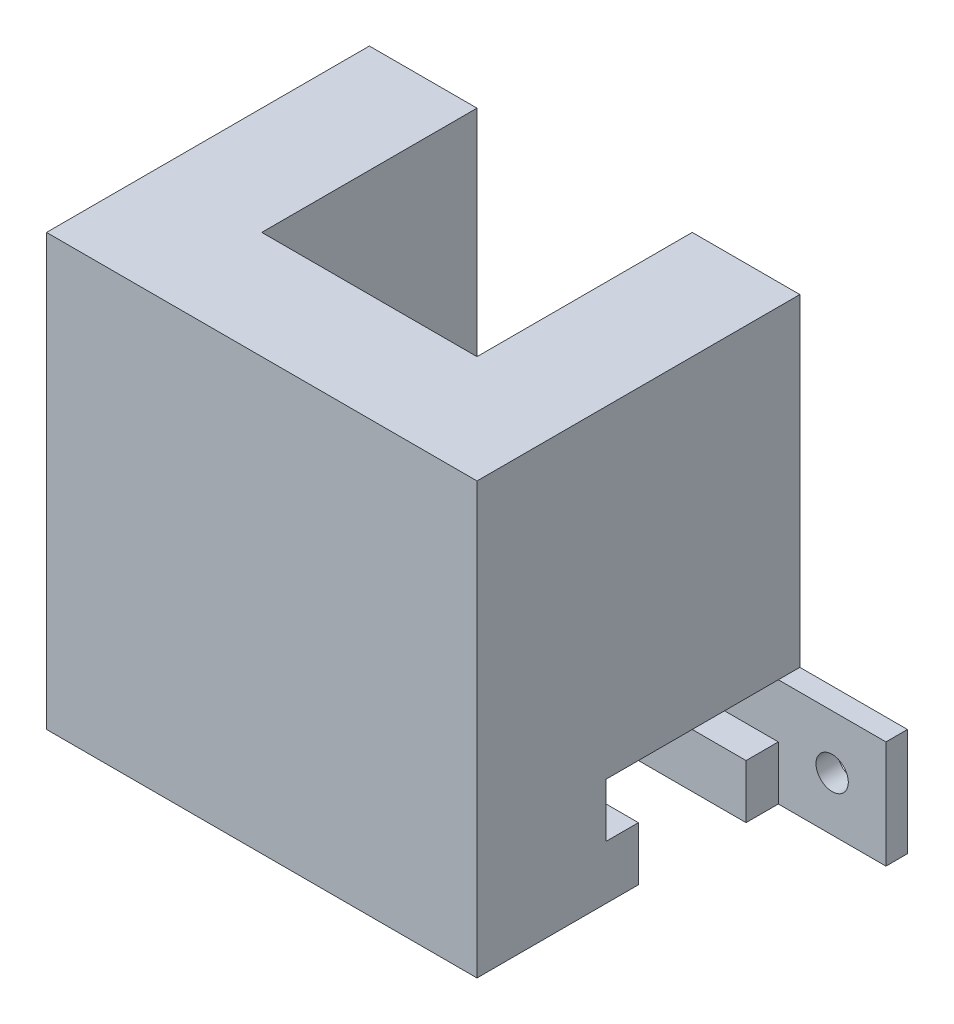
SolidWorks part; units mm, degrees
ref_plane "Front Plane" through (0, 0, 0) normal (0, 0, 1) x (1, 0, 0)
ref_plane "Top Plane" through (0, 0, 0) normal (0, 1, 0) x (1, 0, 0)
ref_plane "Right Plane" through (0, 0, 0) normal (1, 0, 0) x (0, 0, -1)
sketch "Sketch1" plane through (0, 0, 0) normal (0, 0, 1) x (1, 0, 0)
  line L1 (-25.0743, -15) -> (14.9257, -15)
  line L2 (-25.0743, -15) -> (-25.0743, 25)
  line L3 (-25.0743, 25) -> (14.9257, 25)
  line L4 (14.9257, -15) -> (14.9257, 25)
  line L5 (-25.0743, -15) -> (14.9257, 25) construction
  line L6 (-25.0743, 25) -> (14.9257, -15) construction
  point P0 (-5.0743, 5)
  dimension "D1" = 40
  dimension "D2" = 40
extrude "Boss-Extrude1" add sketch "Sketch1" along normal blind 30
sketch "Sketch2" plane through (0, 0, 0) normal (0, 0, -1) x (-1, 0, 0)
  line L0 (25.0743, -15) -> (-14.9257, -15) construction
  line L1 (-4.9257, 25) -> (15.0743, 25)
  line L2 (-4.9257, 25) -> (-4.9257, 5)
  line L3 (-4.9257, 5) -> (15.0743, 5)
  line L4 (15.0743, 25) -> (15.0743, 5)
  line L5 (25.0743, 25) -> (25.0743, -15) construction
  dimension "2" = 20
  dimension "D2" = 20
  dimension "D3" = 20
  dimension "D4" = 10
extrude "Cut-Extrude1" cut sketch "Sketch2" against normal blind 20
sketch "Sketch5" plane through (0, 5, 0) normal (0, 1, 0) x (1, 0, 0)
  line L0 (4.9257, 0) -> (-15.0743, 0) construction
  line L1 (-15.0743, -20) -> (-15.0743, 0) construction
  circle A0 centre (-5.0743, -10) radius 1.8
  dimension "D1" = 3.6
  dimension "D2" = 10
  dimension "D3" = 10
extrude "Cut-Extrude6" cut sketch "Sketch5" against normal blind 20
ref_plane "Plane4" through (0, 0, 10) normal (0, 0, 1) x (1, 0, 0)
sketch "Sketch24" plane through (0, 0, 10) normal (0, 0, 1) x (1, 0, 0)
  line L0 (-3.2743, -5) -> (-5.0743, -5)
  line L1 (4.9257, 5) -> (-15.0743, 5) construction
  line L3 (4.9257, 5) -> (-3.2743, -5)
  line L5 (4.9257, 5) -> (-5.0743, 5)
  line L6 (-5.0743, 5) -> (-5.0743, -5)
  dimension "D2" = 10
revolve "Cut-Revolve1" cut sketch "Sketch24" angle 360 about L6
sketch "Sketch25" plane through (-25.0743, 0, 0) normal (-1, 0, 0) x (0, 0, 1)
  line L1 (0, -15) -> (2, -15)
  line L2 (0, -15) -> (0, -5)
  line L3 (0, -5) -> (2, -5)
  line L4 (2, -15) -> (2, -5)
  dimension "D1" = 10
  dimension "D2" = 2
extrude "Boss-Extrude2" add sketch "Sketch25" along normal blind 10
sketch "Sketch26" plane through (14.9257, 0, 0) normal (1, 0, 0) x (0, 0, -1)
  line L1 (0, -15) -> (-2, -15)
  line L2 (0, -15) -> (0, -5)
  line L3 (0, -5) -> (-2, -5)
  line L4 (-2, -15) -> (-2, -5)
  dimension "D1" = 10
  dimension "D2" = 2
extrude "Boss-Extrude3" add sketch "Sketch26" along normal blind 10
sketch "Sketch27" plane through (0, 0, 0) normal (0, 0, -1) x (-1, 0, 0)
  line L0 (35.0743, -15) -> (-24.9257, -15) construction
  line L1 (-24.9257, -15) -> (-24.9257, -5) construction
  line L2 (35.0743, -5) -> (35.0743, -15) construction
  circle A0 centre (-19.9257, -10) radius 1.5
  circle A1 centre (30.0743, -10) radius 1.5
  dimension "D5" = 3
  dimension "D6" = 3
  dimension "D1" = 5
  dimension "D2" = 5
  dimension "D3" = 5
  dimension "D4" = 5
extrude "Cut-Extrude7" cut sketch "Sketch27" against normal blind 10
sketch "Sketch28" plane through (14.9257, 0, 0) normal (1, 0, 0) x (0, 0, -1)
  line L0 (-30, -15) -> (-2, -15) construction
  line L2 (-15, -10) -> (-15, -15)
  line L3 (-15, -15) -> (-5, -15)
  line L4 (-5, -10) -> (-5, -15)
  line L5 (0, -5) -> (0, 25) construction
  line L6 (-2, -5) -> (-2, -15) construction
  line L7 (-18, -5) -> (-2, -5)
  line L8 (-18, -5) -> (-18, -10)
  line L9 (-18, -10) -> (-15, -10)
  line L10 (-2, -5) -> (-2, -10)
  line L11 (-5, -10) -> (-2, -10)
  dimension "D1" = 10
  dimension "D2" = 5
  dimension "D4" = 5
  dimension "D5" = 5
  dimension "D6" = 16
extrude "Cut-Extrude8" cut sketch "Sketch28" against normal blind 10
sketch "Sketch29" plane through (-25.0743, 0, 0) normal (-1, 0, 0) x (0, 0, 1)
  line L11 (30, -15) -> (2, -15) construction
  line L12 (5, -15) -> (15, -15)
  line L13 (5, -15) -> (5, -10)
  line L15 (15, -15) -> (15, -10)
  line L16 (0, -5) -> (0, -15) construction
  line L17 (15, -10) -> (18, -10)
  line L18 (2, -5) -> (18, -5)
  line L19 (2, -5) -> (2, -10)
  line L20 (2, -10) -> (5, -10)
  line L21 (18, -5) -> (18, -10)
  dimension "D1" = 10
  dimension "D2" = 5
  dimension "D3" = 5
  dimension "D5" = 16
extrude "Cut-Extrude9" cut sketch "Sketch29" against normal blind 10
sketch "Sketch30" plane through (0, -15, 0) normal (0, -1, 0) x (1, 0, 0)
  circle A0 centre (-5.0743, 10) radius 3
  dimension "D1" = 6
extrude "Cut-Extrude10" cut sketch "Sketch30" against normal blind 5
